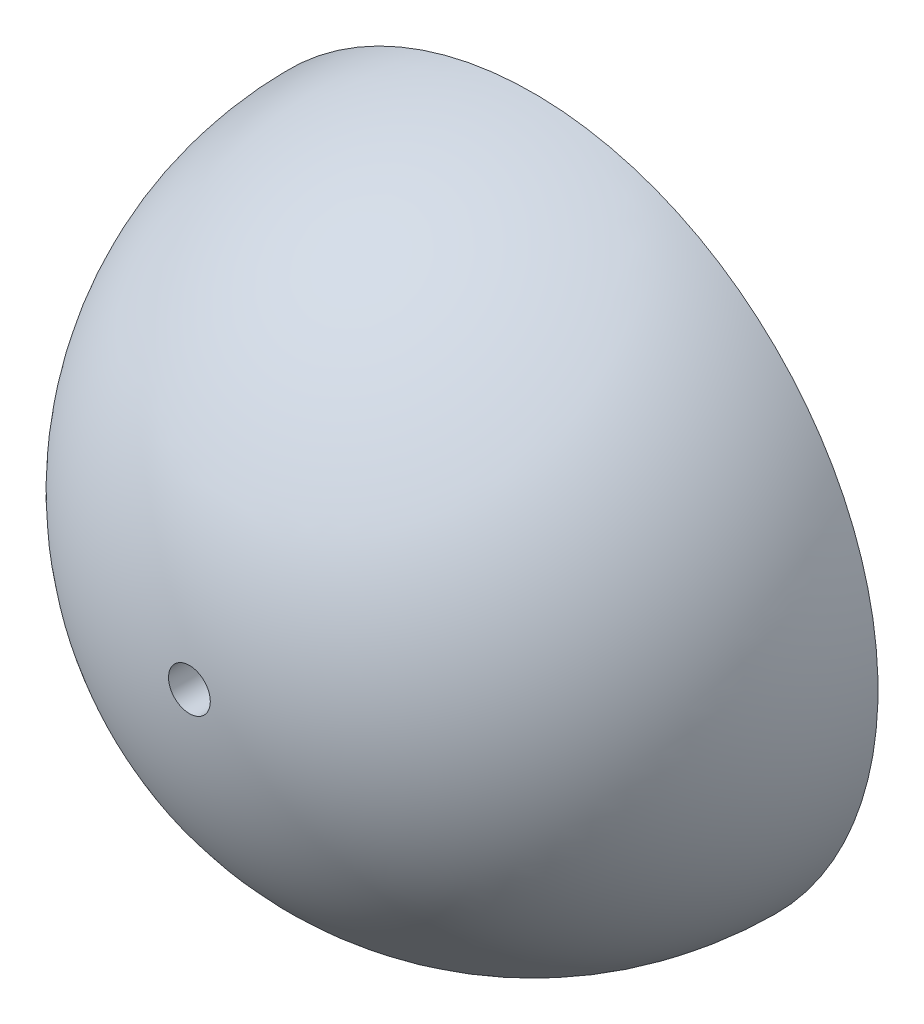
SolidWorks part; units mm, degrees
ref_plane "Front Plane" through (0, 0, 0) normal (0, 0, 1) x (1, 0, 0)
ref_plane "Top Plane" through (0, 0, 0) normal (0, 1, 0) x (1, 0, 0)
ref_plane "Right Plane" through (0, 0, 0) normal (1, 0, 0) x (0, 0, -1)
sketch "Sketch1" plane through (0, 0, 0) normal (0, 0, 1) x (1, 0, 0)
  line L0 (0, -825) -> (0, 825) construction
  line L1 (0, 825) -> (0, 700)
  line L2 (0, -700) -> (0, -825)
  arc A0 (0, -825) -> (0, 825) centre (0, 0) ccw
  arc A1 (0, -700) -> (0, 700) centre (0, 0) ccw
  point P4 (0, 0)
  dimension "D2" = 1400
  dimension "D1" = 1650
revolve "Revolve1" add sketch "Sketch1" angle 180 about L2
sketch "Sketch2" plane through (0, 0, 0) normal (0, 0, 1) x (1, 0, 0)
  circle A0 centre (0, 0) radius 50
  dimension "D1" = 100
extrude "Cut-Extrude5" cut sketch "Sketch2" against normal through all and the other way through all contours A0
